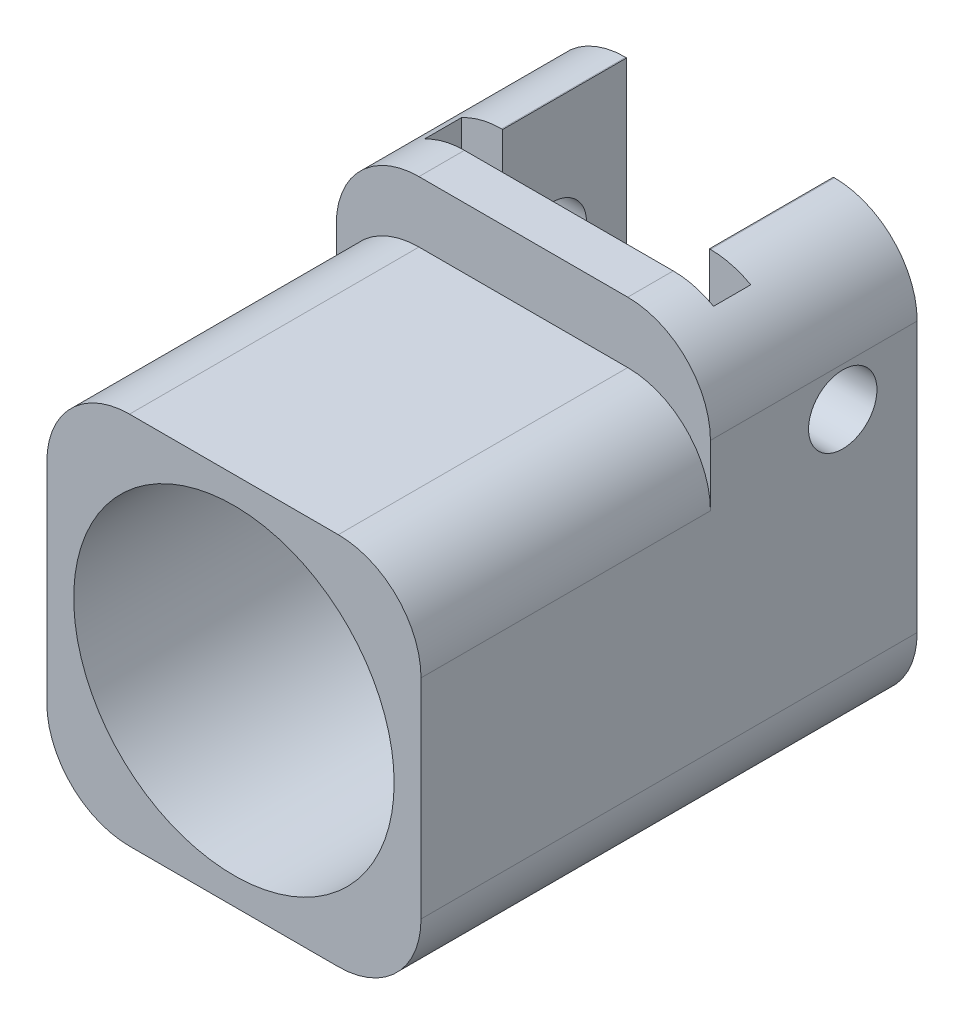
SolidWorks part; units mm, degrees
ref_plane "Front Plane" through (0, 0, 0) normal (0, 0, 1) x (1, 0, 0)
ref_plane "Top Plane" through (0, 0, 0) normal (0, 1, 0) x (1, 0, 0)
ref_plane "Right Plane" through (0, 0, 0) normal (1, 0, 0) x (0, 0, -1)
sketch "Sketch1" plane through (0, 0, 0) normal (0, 0, 1) x (1, 0, 0)
  line L0 (-5.05, 9.05) -> (5.05, 9.05)
  line L1 (9.05, -5.05) -> (9.05, 5.05)
  line L2 (0, 0) -> (0, 14.1446) construction
  line L3 (-9.05, -5.05) -> (-9.05, 5.05)
  line L4 (-12.732, 0) -> (15.0845, 0) construction
  line L5 (-5.05, -9.05) -> (5.05, -9.05)
  arc A4 (5.05, 9.05) -> (9.05, 5.05) centre (5.05, 5.05) cw
  arc A5 (9.05, -5.05) -> (5.05, -9.05) centre (5.05, -5.05) cw
  arc A6 (-5.05, -9.05) -> (-9.05, -5.05) centre (-5.05, -5.05) cw
  arc A7 (-9.05, 5.05) -> (-5.05, 9.05) centre (-5.05, 5.05) cw
  point P11 (9.05, 0)
  point P12 (0, 9.05)
  point P20 (0, -9.05)
  point P21 (-9.05, 0)
  dimension "D3" = 0
  dimension "D1" = 5.05
  dimension "D2" = 5.05
  dimension "D4" = 9.05
  dimension "D5" = 9.05
extrude "Boss-Extrude1" add sketch "Sketch1" along normal blind 24
sketch "Sketch15" plane through (0, 0, 0) normal (0, 0, 1) x (1, 0, 0)
  line L0 (9.05, -5.05) -> (9.05, 5.05) construction
  line L6 (-5.05, -9.05) -> (5.05, -9.05)
  line L7 (-9.05, -5.05) -> (-9.05, 8)
  line L8 (-5.05, 12) -> (5.05, 12)
  line L9 (9.05, -5.05) -> (9.05, 8)
  line L10 (-5.05, -9.05) -> (5.05, -9.05) construction
  line L11 (-9.05, -5.05) -> (-9.05, 5.05) construction
  arc A4 (-5.05, -9.05) -> (-9.05, -5.05) centre (-5.05, -5.05) cw
  arc A5 (5.05, -9.05) -> (9.05, -5.05) centre (5.05, -5.05) ccw
  arc A6 (5.05, 12) -> (9.05, 8) centre (5.05, 8) cw
  arc A7 (-9.05, 8) -> (-5.05, 12) centre (-5.05, 8) cw
  point P0 (0, 0)
  dimension "D2" = 0
  dimension "D5" = 4
  dimension "D1" = 12
  dimension "D3" = 0
  dimension "D4" = 0
extrude "Boss-Extrude3" add sketch "Sketch15" along normal blind 10
sketch "Sketch17" plane through (9.05, 0, 0) normal (1, 0, 0) x (0, 0, -1)
  line L2 (0, -5.05) -> (0, 5.05) construction
  line L3 (-10, 12) -> (0, 12) construction
  circle A0 centre (-3.6, 6.1) radius 1.655
  dimension "D1" = 3.31
  dimension "D2" = 3.6
  dimension "D3" = 5.9
extrude "Cut-Extrude10" cut sketch "Sketch17" against normal blind 30
sketch "Sketch18" plane through (0, 0, 0) normal (0, 0, 1) x (1, 0, 0)
  line L82 (-4.9965, -4.2592) -> (-3.8511, -6.9461)
  line L83 (-3.8511, -6.9461) -> (-2.0485, -4.5591)
  line L86 (-2.0485, -4.5591) -> (-0.5631, -7.2172)
  line L87 (-0.5631, -7.2172) -> (0.9839, -4.6242)
  line L88 (0.9839, -4.6242) -> (2.7048, -7.2172)
  line L91 (2.7048, -7.2172) -> (3.4697, -4.8701)
  line L92 (3.4697, -4.8701) -> (4.6745, -7.0261)
  line L93 (4.6745, -7.0261) -> (4.9982, -5.6687)
  line L94 (-4.9965, -4.2592) -> (-4.9965, 5.3735)
  line L95 (-4.9965, 5.3735) -> (4.9982, 5.3735)
  line L96 (4.9982, 5.3735) -> (4.9982, -5.6687)
  dimension "D1" = 4.9965
  dimension "D2" = 4.9982
extrude "Cut-Extrude11" cut sketch "Sketch18" along normal blind 6
sketch "Sketch20" plane through (0, 0, 6) normal (0, 0, -1) x (-1, 0, 0)
  line L0 (-7, 0) -> (-7, 13.4738)
  line L1 (-7, 13.4738) -> (7, 13.4738)
  line L2 (7, 13.4738) -> (7, 0)
  line L3 (-7, 0) -> (-7, -7.1944)
  line L4 (-7, -7.1944) -> (7, -7.1944)
  line L5 (7, -7.1944) -> (7, 0)
  dimension "D2" = 7
extrude "Cut-Extrude12" cut sketch "Sketch20" against normal blind 1.8
sketch "Sketch21" plane through (0, 0, 0) normal (0, 0, 1) x (1, 0, 0)
  line L0 (-12.732, 0) -> (15.0845, 0) construction
  line L3 (5, 17.4937) -> (-5, 17.4937)
  line L4 (-5, 0) -> (-5, 17.4937)
  line L8 (5, 0) -> (5, -0.5)
  line L9 (5, -0.5) -> (-5, -0.5)
  line L10 (-5, -0.5) -> (-5, 0)
  line L11 (5, 0) -> (5, 17.4937)
  dimension "D1" = 5
  dimension "D2" = 5
  dimension "D3" = 0.5
extrude "Cut-Extrude13" cut sketch "Sketch21" along normal blind 7.2
sketch "Sketch24" plane through (0, 0, 24) normal (0, 0, 1) x (1, 0, 0)
  circle A0 centre (0, 0) radius 7.75
  dimension "D1" = 15.5
extrude "Cut-Extrude15" cut sketch "Sketch24" against normal blind 14
